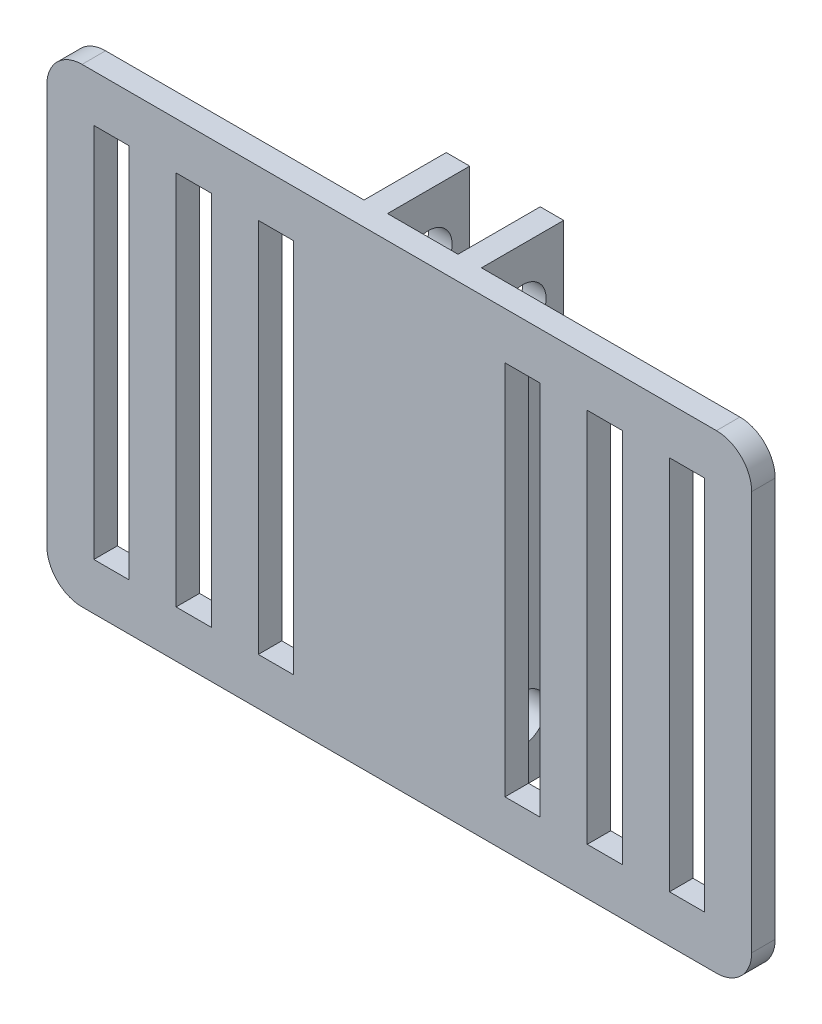
SolidWorks part; units mm, degrees
ref_plane "Plan de face" through (0, 0, 0) normal (0, 0, 1) x (1, 0, 0)
ref_plane "Plan de dessus" through (0, 0, 0) normal (0, 1, 0) x (1, 0, 0)
ref_plane "Plan de droite" through (0, 0, 0) normal (1, 0, 0) x (0, 0, -1)
sketch "Esquisse1" plane through (0, 0, 0) normal (0, 0, 1) x (1, 0, 0)
  line L1 (0, 0) -> (60, 0)
  line L2 (0, 0) -> (0, 40)
  line L3 (0, 40) -> (60, 40)
  line L4 (60, 0) -> (60, 40)
extrude "Boss.-Extru.1" add sketch "Esquisse1" along normal blind 9
sketch "Esquisse2" plane through (0, 0, 0) normal (0, 0, -1) x (-1, 0, 0)
  line L1 (-25, 40) -> (0, 40)
  line L2 (-25, 40) -> (-25, 0)
  line L3 (-25, 0) -> (0, 0)
  line L4 (0, 40) -> (0, 0)
  line L5 (-60, 40) -> (-35, 40)
  line L6 (-60, 40) -> (-60, 0)
  line L7 (-60, 0) -> (-35, 0)
  line L8 (-35, 40) -> (-35, 0)
  line L9 (-27, 40) -> (-33, 40)
  line L10 (-27, 40) -> (-27, 0)
  line L11 (-27, 0) -> (-33, 0)
  line L12 (-33, 40) -> (-33, 0)
extrude "Enlèv. mat.-Extru.1" cut sketch "Esquisse2" against normal blind 7
sketch "Esquisse3" plane through (35, 0, 0) normal (1, 0, 0) x (0, 0, -1)
  circle A0 centre (-3.5, 5) radius 2
  circle A1 centre (-3.5, 35) radius 2
  point P2 (0, 0)
  point P5 (-3.5655, 34.6493)
  point P6 (0, 0)
extrude "Enlèv. mat.-Extru.2" cut sketch "Esquisse3" against normal through all
sketch "Esquisse4" plane through (0, 0, 7) normal (0, 0, -1) x (-1, 0, 0)
  line L0 (-49, 36) -> (-49, 4)
  line L1 (-56, 36) -> (-53, 36)
  line L2 (-56, 36) -> (-56, 4)
  line L3 (-56, 4) -> (-53, 4)
  line L4 (-53, 36) -> (-53, 4)
  line L5 (-46, 36) -> (-46, 4)
  line L6 (-49, 36) -> (-46, 36)
  line L7 (-49, 4) -> (-46, 4)
  line L8 (-42, 36) -> (-42, 4)
  line L9 (-39, 36) -> (-39, 4)
  line L10 (-42, 36) -> (-39, 36)
  line L11 (-42, 4) -> (-39, 4)
  line L12 (-11, 36) -> (-11, 4)
  line L13 (-4, 36) -> (-7, 36)
  line L14 (-4, 36) -> (-4, 4)
  line L15 (-4, 4) -> (-7, 4)
  line L16 (-7, 36) -> (-7, 4)
  line L17 (-11, 36) -> (-14, 36)
  line L18 (-14, 36) -> (-14, 4)
  line L19 (-11, 4) -> (-14, 4)
  line L20 (-18, 36) -> (-18, 4)
  line L21 (-18, 36) -> (-21, 36)
  line L22 (-21, 36) -> (-21, 4)
  line L23 (-18, 4) -> (-21, 4)
  dimension "D1" = 3
  dimension "D2" = 3
extrude "Enlèv. mat.-Extru.3" cut sketch "Esquisse4" against normal through all
fillet "Congé1" radius 3 4 edges at (0, 0, 8) (60, 0, 8) (0, 40, 8) (60, 40, 8)
